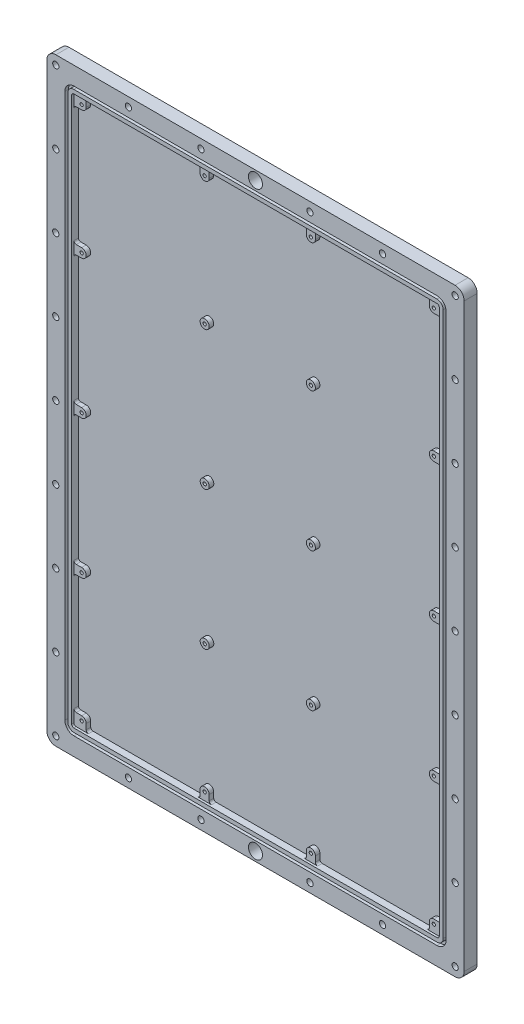
SolidWorks part; units mm, degrees
ref_plane "Front Plane" through (0, 0, 0) normal (0, 0, 1) x (1, 0, 0)
ref_plane "Top Plane" through (0, 0, 0) normal (0, 1, 0) x (1, 0, 0)
ref_plane "Right Plane" through (0, 0, 0) normal (1, 0, 0) x (0, 0, -1)
sketch "Sketch1" plane through (0, 0, 0) normal (0, 0, 1) x (1, 0, 0)
  line L1 (0, 0) -> (291.973, 0)
  line L2 (0, 0) -> (0, 418.973)
  line L3 (0, 418.973) -> (291.973, 418.973)
  line L4 (291.973, 0) -> (291.973, 418.973)
  dimension "D1" = 418.973
  dimension "D2" = 291.973
extrude "Boss-Extrude1" add sketch "Sketch1" along normal blind 9.144
sketch "Sketch4" plane through (0, 0, 9.144) normal (0, 0, 1) x (1, 0, 0)
  line L0 (91.477, 6.2865) -> (91.477, 0) construction
  line L1 (0, 0) -> (291.973, 0) construction
  line L2 (6.2865, 94.9672) -> (0, 94.9672) construction
  line L4 (6.2865, 412.6865) -> (285.6865, 412.6865) construction
  line L5 (6.2865, 412.6865) -> (6.2865, 6.2865) construction
  line L6 (6.2865, 6.2865) -> (285.6865, 6.2865) construction
  line L7 (285.6865, 412.6865) -> (285.6865, 6.2865) construction
  line L11 (0, 418.973) -> (0, 0) construction
  line L12 (285.6865, 110.613) -> (291.973, 110.613) construction
  line L13 (291.973, 0) -> (291.973, 418.973) construction
  line L14 (125.5626, 412.6865) -> (125.5626, 418.973) construction
  line L15 (291.973, 418.973) -> (0, 418.973) construction
  circle A0 centre (6.2865, 6.2865) radius 2.1844
  circle A1 centre (6.2865, 412.6865) radius 2.1844
  circle A2 centre (285.6865, 412.6865) radius 2.1844
  circle A3 centre (285.6865, 6.2865) radius 2.1844
  dimension "D5" = 4.3688
  dimension "D1" = 279.4
  dimension "D2" = 406.4
extrude "Cut-Extrude1" cut sketch "Sketch4" against normal through all
sketch "Sketch5" plane through (0, 0, 9.144) normal (0, 0, 1) x (1, 0, 0)
  line L0 (0, 209.4865) -> (12.6365, 209.4865) construction
  line L1 (18.9865, 406.3365) -> (272.9865, 406.3365)
  line L2 (12.6365, 399.9865) -> (12.6365, 18.9865)
  line L3 (18.9865, 12.6365) -> (272.9865, 12.6365)
  line L4 (279.3365, 399.9865) -> (279.3365, 18.9865)
  line L5 (0, 418.973) -> (0, 0) construction
  line L6 (279.3365, 209.4865) -> (291.973, 209.4865) construction
  line L8 (18.9865, 14.6685) -> (272.9865, 14.6685)
  line L9 (14.6685, 399.9865) -> (14.6685, 18.9865)
  line L10 (18.9865, 404.3045) -> (272.9865, 404.3045)
  line L11 (277.3045, 399.9865) -> (277.3045, 18.9865)
  line L12 (291.973, 0) -> (291.973, 418.973) construction
  line L13 (145.9865, 12.6365) -> (145.9865, 0) construction
  line L14 (0, 0) -> (291.973, 0) construction
  line L15 (145.9865, 406.3365) -> (145.9865, 418.973) construction
  line L16 (291.973, 418.973) -> (0, 418.973) construction
  arc A0 (272.9865, 12.6365) -> (279.3365, 18.9865) centre (272.9865, 18.9865) ccw
  arc A1 (12.6365, 18.9865) -> (18.9865, 12.6365) centre (18.9865, 18.9865) ccw
  arc A2 (272.9865, 406.3365) -> (279.3365, 399.9865) centre (272.9865, 399.9865) cw
  arc A3 (18.9865, 406.3365) -> (12.6365, 399.9865) centre (18.9865, 399.9865) ccw
  arc A4 (14.6685, 18.9865) -> (18.9865, 14.6685) centre (18.9865, 18.9865) ccw
  arc A5 (18.9865, 404.3045) -> (14.6685, 399.9865) centre (18.9865, 399.9865) ccw
  arc A6 (272.9865, 404.3045) -> (277.3045, 399.9865) centre (272.9865, 399.9865) cw
  arc A7 (272.9865, 14.6685) -> (277.3045, 18.9865) centre (272.9865, 18.9865) ccw
  dimension "D5" = 6.35
  dimension "D1" = 266.7
  dimension "D2" = 393.7
  dimension "D6" = 2.032
  dimension "D7" = 2.032
extrude "Cut-Extrude2" cut sketch "Sketch5" against normal blind 2.54 contours L1 A3 L2 A1 L3 A0 L4 A2 A7 L8 A4 L9 A5 L10 A6 L11
pattern_linear "LPattern4" count 8 spacing 50.8 along (0, -1, 0) of "Cut-Extrude1"
sketch "Sketch6" plane through (0, 0, 9.144) normal (0, 0, 1) x (1, 0, 0)
  line L4 (274.574, 18.9865) -> (274.574, 399.9865)
  line L5 (274.574, 18.9865) -> (274.574, 399.9865)
  line L6 (272.9865, 401.574) -> (18.9865, 401.574)
  line L7 (272.9865, 401.574) -> (18.9865, 401.574)
  line L8 (17.399, 399.9865) -> (17.399, 18.9865)
  line L9 (17.399, 399.9865) -> (17.399, 18.9865)
  line L10 (18.9865, 17.399) -> (272.9865, 17.399)
  line L11 (18.9865, 17.399) -> (272.9865, 17.399)
  arc A4 (272.9865, 17.399) -> (274.574, 18.9865) centre (272.9865, 18.9865) ccw
  arc A5 (272.9865, 17.399) -> (274.574, 18.9865) centre (272.9865, 18.9865) ccw
  arc A6 (274.574, 399.9865) -> (272.9865, 401.574) centre (272.9865, 399.9865) ccw
  arc A7 (274.574, 399.9865) -> (272.9865, 401.574) centre (272.9865, 399.9865) ccw
  arc A8 (18.9865, 401.574) -> (17.399, 399.9865) centre (18.9865, 399.9865) ccw
  arc A9 (18.9865, 401.574) -> (17.399, 399.9865) centre (18.9865, 399.9865) ccw
  arc A10 (17.399, 18.9865) -> (18.9865, 17.399) centre (18.9865, 18.9865) ccw
  arc A11 (17.399, 18.9865) -> (18.9865, 17.399) centre (18.9865, 18.9865) ccw
  dimension "D1" = 2.7305
extrude "Cut-Extrude3" cut sketch "Sketch6" against normal blind 4.7625
sketch "Sketch7" plane through (0, 0, 4.3815) normal (0, 0, 1) x (1, 0, 0)
  line L0 (272.9865, 401.574) -> (18.9865, 401.574) construction
  line L1 (22.7965, 396.1765) -> (269.1765, 396.1765) construction
  line L2 (22.7965, 396.1765) -> (22.7965, 22.7965) construction
  line L3 (22.7965, 22.7965) -> (269.1765, 22.7965) construction
  line L4 (269.1765, 396.1765) -> (269.1765, 22.7965) construction
  line L5 (17.399, 399.9865) -> (17.399, 18.9865) construction
  line L6 (274.574, 18.9865) -> (274.574, 399.9865) construction
  line L7 (269.1765, 112.6109) -> (22.7965, 112.6109) construction
  line L8 (17.399, 399.9865) -> (17.399, 18.9865) construction
  line L9 (274.574, 18.9865) -> (274.574, 399.9865) construction
  line L10 (269.1765, 209.4865) -> (22.7965, 209.4865) construction
  line L11 (183.1213, 396.1765) -> (183.1213, 22.7965) construction
  line L12 (108.8517, 22.7965) -> (108.8517, 396.1765) construction
  line L13 (269.1765, 306.3621) -> (22.7965, 306.3621) construction
  line L16 (18.9865, 17.399) -> (272.9865, 17.399) construction
  circle A0 centre (22.7965, 396.1765) radius 1.1303
  circle A1 centre (269.1765, 396.1765) radius 1.1303
  circle A2 centre (22.7965, 22.7965) radius 1.1303
  circle A3 centre (108.8517, 22.7965) radius 1.1303
  circle A4 centre (108.8517, 396.1765) radius 1.1303
  circle A5 centre (183.1213, 396.1765) radius 1.1303
  circle A6 centre (183.1213, 22.7965) radius 1.1303
  circle A7 centre (269.1765, 22.7965) radius 1.1303
  circle A8 centre (269.1765, 112.6109) radius 1.1303
  circle A9 centre (108.8898, 112.6109) radius 1.1303
  circle A10 centre (183.1594, 112.6109) radius 1.1303
  circle A11 centre (22.7965, 112.6109) radius 1.1303
  circle A12 centre (269.1765, 209.4865) radius 1.1303
  circle A13 centre (108.8898, 209.4865) radius 1.1303
  circle A14 centre (183.1594, 209.4865) radius 1.1303
  circle A15 centre (22.7965, 209.4865) radius 1.1303
  circle A16 centre (269.1765, 306.3621) radius 1.1303
  circle A17 centre (108.8517, 306.3621) radius 1.1303
  circle A18 centre (183.1213, 306.3621) radius 1.1303
  circle A19 centre (22.7965, 306.3621) radius 1.1303
  dimension "D5" = 2.2606
  dimension "D11" = 96.8756
  dimension "D9" = 373.38
  dimension "D13" = 86.0552
  dimension "D14" = 86.0552
  dimension "D1" = 5.3975
  dimension "D2" = 5.3975
  dimension "D3" = 5.3975
  dimension "D4" = 5.3975
  dimension "D6" = 91.4527
  dimension "D7" = 91.4527
  dimension "D8" = 91.4527
  dimension "D10" = 96.8756
  dimension "D12" = 91.4527
extrude "Cut-Extrude4" cut sketch "Sketch7" against normal blind 1.5875
fillet "Fillet1" radius 6.35 4 edges at (291.973, 0, 4.572) (0, 0, 4.572) (291.973, 418.973, 4.572) (0, 418.973, 4.572)
sketch "Sketch10" plane through (0, 0, 0) normal (0, 0, -1) x (-1, 0, 0)
  line L0 (-285.6865, 412.6865) -> (-6.2865, 412.6865) construction
  circle A0 centre (-234.8865, 412.6865) radius 2.1844
  circle A1 centre (-184.0865, 412.6865) radius 2.1844
  circle A2 centre (-107.8865, 412.6865) radius 2.1844
  circle A3 centre (-57.0865, 412.6865) radius 2.1844
  circle A4 centre (-285.6865, 412.6865) radius 2.1844 construction
  circle A5 centre (-145.9865, 412.6865) radius 4.9022
  dimension "D5" = 9.8044
  dimension "D1" = 50.8
  dimension "D2" = 50.8
  dimension "D3" = 50.8
  dimension "D4" = 50.8
extrude "Cut-Extrude7" cut sketch "Sketch10" against normal through all
pattern_linear "LPattern5" count 2 spacing 406.4 along (0, -1, 0) of "Cut-Extrude7"
chamfer "Chamfer1" distance 2.54 angle 41 26 edges at (287.8709, 158.6865, 0) (287.8709, 209.4865, 0) (287.8709, 260.2865, 0) (287.8709, 311.0865, 0) (287.8709, 361.8865, 0) (287.8709, 107.8865, 0) (287.8709, 57.0865, 0) (287.8709, 6.2865, 0) (232.7021, 6.2865, 0) (181.9021, 6.2865, 0) (105.7021, 6.2865, 0) (54.9021, 6.2865, 0) (8.4709, 6.2865, 0) (8.4709, 57.0865, 0) (8.4709, 107.8865, 0) (8.4709, 158.6865, 0) (8.4709, 209.4865, 0) (8.4709, 260.2865, 0) (8.4709, 311.0865, 0) (8.4709, 361.8865, 0) (8.4709, 412.6865, 0) (54.9021, 412.6865, 0) (105.7021, 412.6865, 0) (181.9021, 412.6865, 0) (232.7021, 412.6865, 0) (287.8709, 412.6865, 0)
sketch "Sketch11" plane through (0, 0, 4.3815) normal (0, 0, 1) x (1, 0, 0)
  line L0 (22.7965, 109.4359) -> (17.399, 109.4359)
  line L1 (17.399, 399.9865) -> (17.399, 18.9865) construction
  line L2 (22.7965, 115.7859) -> (17.399, 115.7859)
  line L3 (17.399, 399.9865) -> (17.399, 18.9865) construction
  line L4 (22.7965, 212.6615) -> (17.399, 212.6615)
  line L5 (22.7965, 206.3115) -> (17.399, 206.3115)
  line L6 (22.7965, 309.5371) -> (17.399, 309.5371)
  line L7 (22.7965, 393.0015) -> (17.399, 393.0015)
  line L8 (22.7965, 303.1871) -> (17.399, 303.1871)
  line L9 (25.9715, 396.1765) -> (25.9715, 401.574)
  line L10 (272.9865, 401.574) -> (18.9865, 401.574) construction
  line L11 (105.6767, 396.1765) -> (105.6767, 401.574)
  line L12 (272.9865, 401.574) -> (18.9865, 401.574) construction
  line L13 (112.0267, 396.1765) -> (112.0267, 401.574)
  line L14 (179.9463, 396.1765) -> (179.9463, 401.574)
  line L15 (186.2963, 396.1765) -> (186.2963, 401.574)
  line L16 (266.0015, 396.1765) -> (266.0015, 401.574)
  line L17 (269.1765, 393.0015) -> (274.574, 393.0015)
  line L18 (274.574, 18.9865) -> (274.574, 399.9865) construction
  line L19 (269.1765, 309.5371) -> (274.574, 309.5371)
  line L20 (269.1765, 303.1871) -> (274.574, 303.1871)
  line L23 (269.1765, 212.6615) -> (274.574, 212.6615)
  line L24 (269.1765, 206.3115) -> (274.574, 206.3115)
  line L25 (269.1765, 115.7859) -> (274.574, 115.7859)
  line L26 (269.1765, 109.4359) -> (274.574, 109.4359)
  line L27 (266.0015, 22.7965) -> (266.0015, 17.399)
  line L28 (18.9865, 17.399) -> (272.9865, 17.399) construction
  line L29 (269.1765, 25.9715) -> (274.574, 25.9715)
  line L30 (274.574, 18.9865) -> (274.574, 399.9865) construction
  line L31 (179.9463, 22.7965) -> (179.9463, 17.399)
  line L32 (18.9865, 17.399) -> (272.9865, 17.399) construction
  line L33 (186.2963, 22.7965) -> (186.2963, 17.399)
  line L34 (105.6767, 22.7965) -> (105.6767, 17.399)
  line L35 (112.0267, 22.7965) -> (112.0267, 17.399)
  line L36 (25.9715, 22.7965) -> (25.9715, 17.399)
  line L37 (22.7965, 25.9715) -> (17.399, 25.9715)
  circle A0 centre (22.7965, 396.1765) radius 3.175
  circle A1 centre (22.7965, 396.1765) radius 1.1303
  circle A2 centre (183.1213, 396.1765) radius 3.175
  circle A3 centre (108.8517, 396.1765) radius 3.175
  circle A4 centre (269.1765, 396.1765) radius 3.175
  circle A5 centre (269.1765, 306.3621) radius 3.175
  circle A6 centre (269.1765, 209.4865) radius 3.175
  circle A7 centre (269.1765, 112.6109) radius 3.175
  circle A8 centre (269.1765, 22.7965) radius 3.175
  circle A9 centre (183.1213, 22.7965) radius 3.175
  circle A10 centre (108.8517, 22.7965) radius 3.175
  circle A11 centre (22.7965, 22.7965) radius 3.175
  circle A12 centre (22.7965, 112.6109) radius 3.175
  circle A13 centre (108.8898, 112.6109) radius 3.175
  circle A14 centre (183.1594, 112.6109) radius 3.175
  circle A15 centre (183.1594, 209.4865) radius 3.175
  circle A16 centre (108.8898, 209.4865) radius 3.175
  circle A17 centre (22.7965, 209.4865) radius 3.175
  circle A18 centre (22.7965, 306.3621) radius 3.175
  circle A19 centre (108.8517, 306.3621) radius 3.175
  circle A20 centre (183.1213, 306.3621) radius 3.175
  circle A21 centre (108.8517, 306.3621) radius 1.1303 construction
  circle A22 centre (108.8517, 396.1765) radius 1.1303
  circle A23 centre (183.1213, 396.1765) radius 1.1303
  circle A24 centre (269.1765, 396.1765) radius 1.1303
  circle A25 centre (269.1765, 306.3621) radius 1.1303
  circle A26 centre (269.1765, 209.4865) radius 1.1303
  circle A27 centre (269.1765, 112.6109) radius 1.1303
  circle A28 centre (269.1765, 22.7965) radius 1.1303
  circle A29 centre (183.1213, 22.7965) radius 1.1303
  circle A30 centre (108.8517, 22.7965) radius 1.1303
  circle A31 centre (22.7965, 22.7965) radius 1.1303
  circle A32 centre (22.7965, 112.6109) radius 1.1303
  circle A33 centre (108.8898, 112.6109) radius 1.1303
  circle A34 centre (183.1594, 112.6109) radius 1.1303
  circle A35 centre (183.1594, 209.4865) radius 1.1303
  circle A36 centre (108.8898, 209.4865) radius 1.1303
  circle A37 centre (22.7965, 209.4865) radius 1.1303
  circle A38 centre (22.7965, 306.3621) radius 1.1303
  circle A39 centre (108.8517, 306.3621) radius 1.1303
  circle A40 centre (183.1213, 306.3621) radius 1.1303
  circle M3 centre (269.1765, 306.3621) radius 1.1303
  circle M4 centre (183.1213, 306.3621) radius 1.1303
  circle M5 centre (108.8517, 306.3621) radius 1.1303
  circle M6 centre (22.7965, 306.3621) radius 1.1303
  circle M7 centre (269.1765, 209.4865) radius 1.1303
  circle M8 centre (183.1594, 209.4865) radius 1.1303
  circle M9 centre (108.8898, 209.4865) radius 1.1303
  circle M10 centre (22.7965, 209.4865) radius 1.1303
  circle M11 centre (269.1765, 112.6109) radius 1.1303
  circle M12 centre (183.1594, 112.6109) radius 1.1303
  circle M13 centre (108.8898, 112.6109) radius 1.1303
  circle M14 centre (22.7965, 112.6109) radius 1.1303
  circle M15 centre (269.1765, 22.7965) radius 1.1303
  circle M16 centre (183.1213, 22.7965) radius 1.1303
  circle M17 centre (108.8517, 22.7965) radius 1.1303
  circle M18 centre (183.1213, 396.1765) radius 1.1303
  circle M19 centre (108.8517, 396.1765) radius 1.1303
  circle M20 centre (22.7965, 22.7965) radius 1.1303
  circle M21 centre (269.1765, 396.1765) radius 1.1303
  circle M22 centre (22.7965, 396.1765) radius 1.1303
  arc M23 (272.9865, 17.399) -> (274.574, 18.9865) centre (272.9865, 18.9865) ccw
  line M24 (274.574, 18.9865) -> (274.574, 399.9865)
  arc M25 (274.574, 399.9865) -> (272.9865, 401.574) centre (272.9865, 399.9865) ccw
  line M26 (272.9865, 401.574) -> (18.9865, 401.574)
  arc M27 (18.9865, 401.574) -> (17.399, 399.9865) centre (18.9865, 399.9865) ccw
  line M28 (17.399, 399.9865) -> (17.399, 18.9865)
  arc M29 (17.399, 18.9865) -> (18.9865, 17.399) centre (18.9865, 18.9865) ccw
  line M30 (18.9865, 17.399) -> (272.9865, 17.399)
  dimension "D1" = 6.35
extrude "Boss-Extrude4" add sketch "Sketch11" along normal blind 3.175 contours A0 L9 L7 M26 M27 M28 | A0 M22 | A3 M19 | A3 L13 L11 M26 | A2 M18 | A2 L15 L14 M26 | A4 M21 | A4 L17 L16 M24 M25 M26 | A5 M3 | A5 L20 L19 M24 | A6 M7 | A6 L24 L23 M24 | A7 M11 | A7 L26 L25 M24 | A8 M15 | A8 L27 L29 M30 M23 M24 | A9 M16 | A9 L31 L33 M30 | A10 M17 | A10 L34 L35 M30 | A11 M20 | A11 L37 L36 M28 M29 M30 | A12 M14 | A12 L2 L0 M28 | A17 M10 | A17 L4 L5 M28 | A18 M6 | A18 L6 L8 M28 | A19 M5 | A20 M4 | A15 M8 | A16 M9 | A13 M13 | A14 M12
fillet "Fillet2" radius 1.5875 28 edges at (274.574, 303.1871, 5.969) (274.574, 309.5371, 5.969) (274.574, 212.6615, 5.969) (274.574, 206.3115, 5.969) (274.574, 109.4359, 5.969) (274.574, 115.7859, 5.969) (274.574, 25.9715, 5.969) (266.0015, 17.399, 5.969) (179.9463, 17.399, 5.969) (186.2963, 17.399, 5.969) (105.6767, 17.399, 5.969) (112.0267, 17.399, 5.969) (17.399, 25.9715, 5.969) (25.9715, 17.399, 5.969) (17.399, 115.7859, 5.969) (17.399, 109.4359, 5.969) (17.399, 212.6615, 5.969) (17.399, 206.3115, 5.969) (17.399, 309.5371, 5.969) (17.399, 303.1871, 5.969) (274.574, 393.0015, 5.969) (266.0015, 401.574, 5.969) (186.2963, 401.574, 5.969) (179.9463, 401.574, 5.969) (112.0267, 401.574, 5.969) (105.6767, 401.574, 5.969) (25.9715, 401.574, 5.969) (17.399, 393.0015, 5.969)
